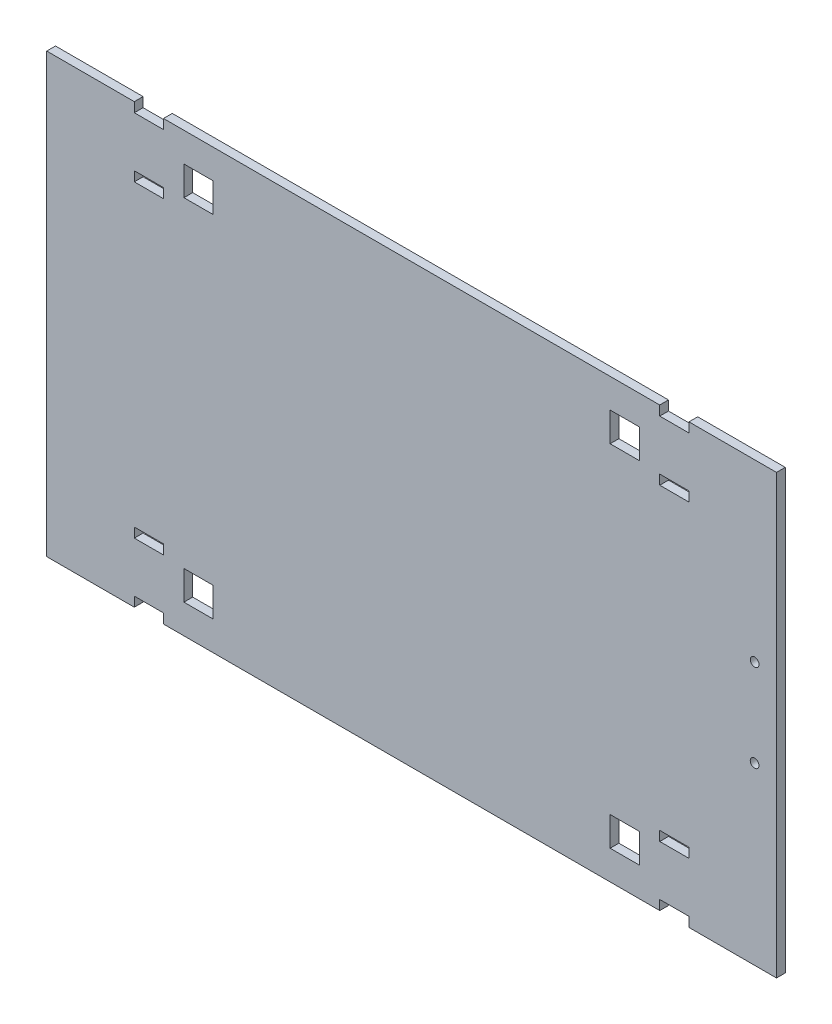
SolidWorks part; units mm, degrees
ref_plane "Front Plane" through (0, 0, 0) normal (0, 0, 1) x (1, 0, 0)
ref_plane "Top Plane" through (0, 0, 0) normal (0, 1, 0) x (1, 0, 0)
ref_plane "Right Plane" through (0, 0, 0) normal (1, 0, 0) x (0, 0, -1)
sketch "Sketch2" plane through (0, 0, 0) normal (0, 0, 1) x (1, 0, 0)
  line L1 (-125, 75) -> (125, 75)
  line L2 (-125, 75) -> (-125, -75)
  line L3 (-125, -75) -> (125, -75)
  line L4 (125, 75) -> (125, -75)
  line L5 (-125, 75) -> (125, -75) construction
  line L6 (-125, -75) -> (125, 75) construction
  point P0 (0, 0)
  dimension "D1" = 250
  dimension "D2" = 150
extrude "Boss-Extrude1" add sketch "Sketch2" along normal blind 3
sketch "Sketch3" plane through (0, 0, 0) normal (0, 0, -1) x (-1, 0, 0)
  line L0 (-61.3588, 0) -> (66.3745, 0) construction
  line L1 (-125, 75) -> (125, 75) construction
  line L2 (-95, 75) -> (-85, 75)
  line L3 (-95, 75) -> (-95, 71.7)
  line L4 (-95, 71.7) -> (-85, 71.7)
  line L5 (-85, 75) -> (-85, 71.7)
  line L6 (-125, -75) -> (-125, 75) construction
  dimension "D1" = 3.3
  dimension "D2" = 10
  dimension "D3" = 30
extrude "Cut-Extrude1" cut sketch "Sketch3" against normal through all and the other way through all
pattern_linear "LPattern1" count 2 spacing 20.5 along (0, -1, 0) of "Cut-Extrude1"
sketch "Sketch4" plane through (0, 0, 0) normal (0, 0, -1) x (-1, 0, 0)
  line L0 (-85, 75) -> (125, 75) construction
  line L1 (-78, 65) -> (-68, 65)
  line L2 (-78, 65) -> (-78, 55)
  line L3 (-78, 55) -> (-68, 55)
  line L4 (-68, 65) -> (-68, 55)
  line L5 (-85, 54.5) -> (-85, 51.2) construction
  point P8 (-85, 52.85)
  dimension "D1" = 10
  dimension "D2" = 10
  dimension "D3" = 10
  dimension "D4" = 7
extrude "Cut-Extrude2" cut sketch "Sketch4" against normal through all
sketch "Sketch5" plane through (0, 0, 0) normal (0, 0, -1) x (-1, 0, 0)
  line L0 (125, 75) -> (125, -75) construction
  line L1 (1.65, 0) -> (-1.65, 0) construction
  circle A0 centre (120, 15) radius 1.5
  circle A1 centre (96, 15) radius 1.5
  dimension "D1" = 3
  dimension "D2" = 5
  dimension "D4" = 24
  dimension "D5" = 15
  dimension "D3" = 15
extrude "Cut-Extrude3" [suppressed] cut sketch "Sketch5" against normal through all
mirror "Mirror1" about plane through (0, 0, 0) normal (0, 1, 0) of "Cut-Extrude3", "Cut-Extrude2", "Cut-Extrude1", "LPattern1"
mirror "Mirror2" about plane through (0, 0, 0) normal (1, 0, 0) of "Mirror1", "LPattern1", "Cut-Extrude1", "Cut-Extrude2"
sketch "Sketch6" plane through (0, 0, 0) normal (0, 0, -1) x (-1, 0, 0)
  line L0 (-125, -75) -> (-125, 75) construction
  circle A0 centre (-117.5, 15) radius 1.5
  dimension "D1" = 3
  dimension "D2" = 7.5
  dimension "D3" = 15
extrude "Cut-Extrude4" cut sketch "Sketch6" against normal through all both and the other way through all
mirror "Mirror3" about plane through (0, 0, 0) normal (0, 1, 0) of "Cut-Extrude4"
